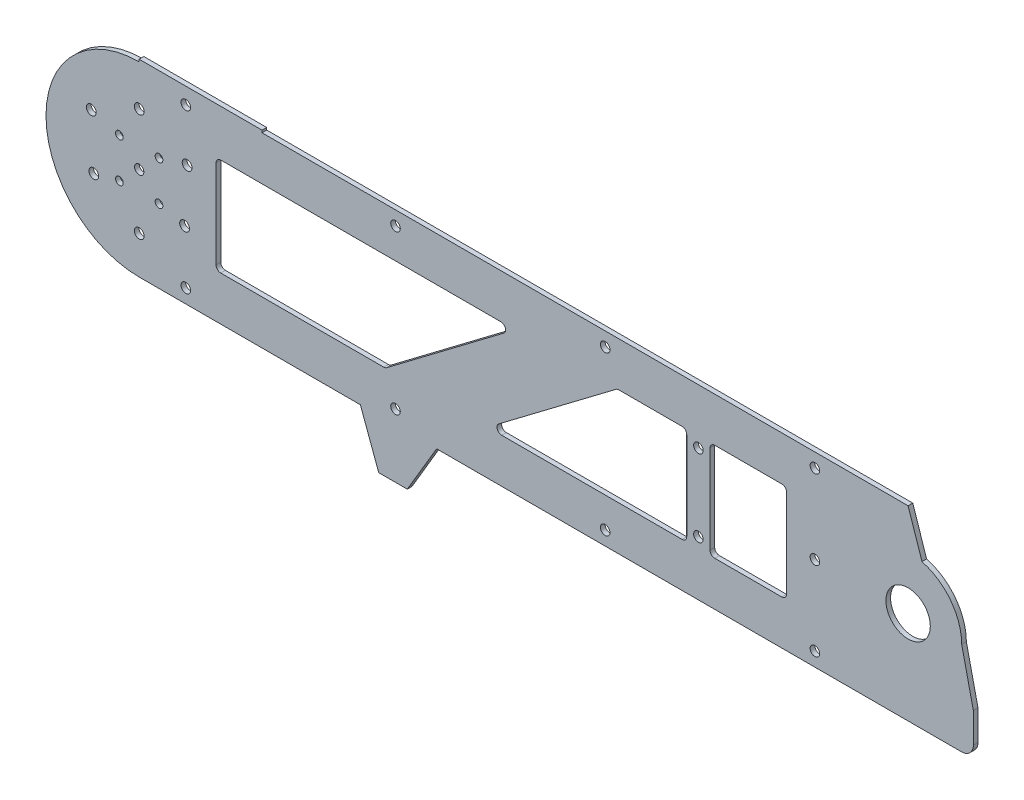
SolidWorks part; units mm, degrees
ref_plane "前视基准面" through (0, 0, 0) normal (0, 0, 1) x (1, 0, 0)
ref_plane "上视基准面" through (0, 0, 0) normal (0, 1, 0) x (1, 0, 0)
ref_plane "右视基准面" through (0, 0, 0) normal (1, 0, 0) x (0, 0, -1)
sketch "草图1" plane through (0, 0, 0) normal (0, 0, 1) x (1, 0, 0)
  line L0 (-1.4571, -0.1457) -> (37.8152, -22.8196) construction
  line L1 (-1.4571, -0.1457) -> (328.5429, -0.1457) construction
  line L8 (-1.4571, 39.8543) -> (328.5429, 39.8543)
  line L9 (-1.4571, -0.1457) -> (-1.4571, -8.6457) construction
  line L10 (-1.4571, -8.6457) -> (7.0429, -8.6457) construction
  line L11 (328.5429, -0.1457) -> (341.7814, 49.2612) construction
  line L12 (328.5429, -0.1457) -> (341.7814, -49.5526) construction
  line L20 (328.5429, 39.8543) -> (334.4957, 22.0706)
  line L23 (356.5429, -48.5797) -> (356.5429, -22.236) construction
  line L35 (113.6085, -61.4457) -> (126.1948, -40.1457)
  line L36 (113.6085, -61.4457) -> (101.3414, -61.4457)
  line L37 (101.3414, -61.4457) -> (93.4628, -40.1457)
  line L38 (93.4628, -40.1457) -> (-1.4571, -40.1457)
  line L39 (126.1948, -40.1457) -> (328.5429, -40.1457)
  line L48 (328.5429, -40.1457) -> (356.5429, -40.1457)
  line L49 (356.5429, -40.1457) -> (356.5429, -22.236)
  line L50 (351.5429, -0.1457) -> (356.5429, -22.236)
  circle A0 centre (-1.4571, -0.1457) radius 23.75 construction
  circle A1 centre (-1.4571, -0.1457) radius 22.5 construction
  circle A2 centre (-1.4571, -23.8957) radius 2.1
  circle A3 centre (18.0284, -11.3957) radius 2.1
  circle A4 centre (-1.4571, -0.1457) radius 40 construction
  circle A6 centre (-1.4571, -0.1457) radius 2
  circle A12 centre (328.5429, -0.1457) radius 40 construction
  arc A16 (-1.4571, -40.1457) -> (-1.4571, 39.8543) centre (-1.4571, -0.1457) cw
  circle A22 centre (328.5429, -0.1457) radius 9.52
  circle A23 centre (288.5429, -0.1457) radius 2.05
  circle A24 centre (238.5429, 16.3543) radius 2.05
  circle A25 centre (238.5429, -16.6457) radius 2.05
  circle A26 centre (-20.9427, -11.3957) radius 2.1
  circle A27 centre (-22.0252, 11.7293) radius 2.1
  circle A28 centre (-1.4571, 22.3543) radius 2.1
  circle A29 centre (19.111, 11.7293) radius 2.1
  circle A36 centre (328.5429, -0.1457) radius 23 construction
  circle A37 centre (7.0429, -8.6457) radius 1.65
  circle A38 centre (-9.9571, -8.6457) radius 1.65
  circle A39 centre (-9.9571, 8.3543) radius 1.65
  circle A40 centre (7.0429, 8.3543) radius 1.65
  arc A45 (334.4957, 22.0706) -> (351.5429, -0.1457) centre (328.5429, -0.1457) cw
  dimension "D1" = 45
  dimension "D2" = 3
  dimension "D3" = 4.2
  dimension "D4" = 19.04
  dimension "D5" = 80
  dimension "D6" = 80
  dimension "D7" = 4
  dimension "D11" = 4.1
  dimension "D12" = 47.5
  dimension "D13" = 4
  dimension "D14" = 105
  dimension "D8" = 330
  dimension "D9" = 50
  dimension "D10" = 16.5
  dimension "D15" = 28
extrude "凸台-拉伸1" add sketch "草图1" along normal blind 2
sketch "草图3" plane through (0, 0, 2) normal (0, 0, 1) x (1, 0, 0)
  line L0 (-1.4571, 39.8543) -> (-1.4571, 40.8343)
  line L5 (-1.4571, 40.8343) -> (51.269, 40.8343)
  line L6 (51.269, 40.8343) -> (51.269, 39.8543)
  line L8 (328.5429, 39.8543) -> (-1.4571, 39.8543) construction
  line L9 (51.269, 39.8543) -> (-1.4571, 39.8543)
  dimension "D4" = 0.98
extrude "凸台-拉伸2" add sketch "草图3" against normal blind 2
sketch "草图2" plane through (0, 0, 2) normal (0, 0, 1) x (1, 0, 0)
  line L0 (18.5429, 33.8543) -> (198.5429, 33.8543) construction
  line L1 (108.5429, -34.1457) -> (198.5429, 33.8543) construction
  line L2 (18.5429, 33.8543) -> (18.5429, -34.1457) construction
  line L3 (18.5429, -34.1457) -> (108.5429, -34.1457) construction
  line L4 (31.5429, -21.1457) -> (104.1839, -21.1457)
  line L5 (104.1839, -21.1457) -> (159.7721, 20.8543)
  line L6 (31.5429, 20.8543) -> (159.7721, 20.8543)
  line L7 (31.5429, 20.8543) -> (31.5429, -21.1457)
  line L8 (108.5429, -34.1457) -> (288.5429, -34.1457) construction
  line L9 (288.5429, -34.1457) -> (288.5429, 33.8543) construction
  line L10 (288.5429, 33.8543) -> (198.5429, 33.8543) construction
  line L11 (276.3527, 20.8543) -> (203.7117, 20.8543) construction
  line L12 (148.1234, -21.1457) -> (203.7117, 20.8543)
  line L13 (148.1234, -21.1457) -> (276.3527, -21.1457) construction
  line L14 (276.3527, -21.1457) -> (276.3527, 20.8543)
  line L15 (233.5429, 20.8543) -> (233.5429, -21.1457)
  line L16 (243.5429, 20.8543) -> (243.5429, -21.1457)
  line L17 (238.5429, 16.3543) -> (238.5429, -16.6457) construction
  line L18 (233.5429, 20.8543) -> (203.7117, 20.8543)
  line L19 (243.5429, 20.8543) -> (276.3527, 20.8543)
  line L20 (243.5429, -21.1457) -> (276.3527, -21.1457)
  line L21 (233.5429, -21.1457) -> (148.1234, -21.1457)
  line L22 (-1.4571, -40.1457) -> (342.5707, -40.1457) construction
  circle A0 centre (18.5429, 33.8543) radius 2.05
  circle A1 centre (108.5429, 33.8543) radius 2.05
  circle A2 centre (198.5429, 33.8543) radius 2.05
  circle A3 centre (288.5429, 33.8543) radius 2.05
  circle A4 centre (108.5429, -34.1457) radius 2.05
  circle A5 centre (198.5429, -34.1457) radius 2.05
  circle A6 centre (288.5429, -34.1457) radius 2.05
  circle A10 centre (18.5429, -34.1457) radius 2.05
  point P2 (-1.4571, -0.1457)
  dimension "D1" = 4.1
  dimension "D14" = 68
  dimension "D2" = 34
  dimension "D3" = 20
  dimension "D4" = 10
  dimension "D13" = 6
extrude "切除-拉伸1" cut sketch "草图2" against normal blind 4
fillet "圆角1" radius 2 12 edges at (243.5429, -21.1457, 1) (243.5429, 20.8543, 1) (276.3527, -21.1457, 1) (276.3527, 20.8543, 1) (233.5429, -21.1457, 1) (233.5429, 20.8543, 1) (203.7117, 20.8543, 1) (148.1234, -21.1457, 1) (159.7721, 20.8543, 1) (104.1839, -21.1457, 1) (31.5429, -21.1457, 1) (31.5429, 20.8543, 1)
fillet "圆角2" radius 5 1 edges at (356.5429, -40.1457, 1)
